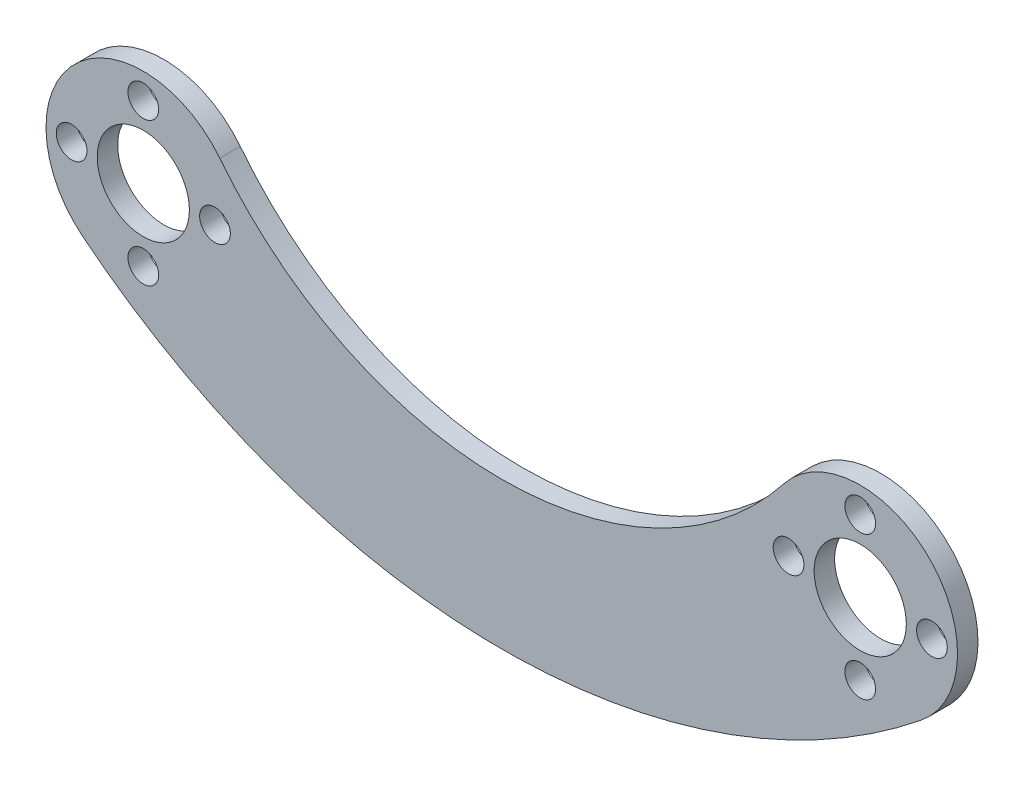
SolidWorks part; units mm, degrees
ref_plane "前视基准面" through (0, 0, 0) normal (0, 0, 1) x (1, 0, 0)
ref_plane "上视基准面" through (0, 0, 0) normal (0, 1, 0) x (1, 0, 0)
ref_plane "右视基准面" through (0, 0, 0) normal (1, 0, 0) x (0, 0, -1)
sketch "草图1" plane through (0, 0, 0) normal (0, 0, 1) x (1, 0, 0)
  line L0 (-54.1945, 0) -> (60.353, 0) construction
  line L1 (0, 45.5042) -> (0, -30.5871) construction
  arc A0 (-27.5281, 5.8669) -> (-40.9709, -7.3891) centre (-35, 0) ccw
  arc A1 (40.9709, -7.3891) -> (27.5281, 5.8669) centre (35, 0) ccw
  arc A2 (-27.5281, 5.8669) -> (27.5281, 5.8669) centre (0, 27.4818) ccw
  arc A3 (-40.9709, -7.3891) -> (40.9709, -7.3891) centre (0, 43.3129) ccw
  dimension "D1" = 19
  dimension "D2" = 19
  dimension "D5" = 35
  dimension "D6" = 65.1867
  dimension "D3" = 70
  dimension "D4" = 35
extrude "凸台-拉伸1" add sketch "草图1" along normal blind 2
sketch "草图2" plane through (0, 0, 2) normal (0, 0, 1) x (1, 0, 0)
  line L0 (-54.4006, 0) -> (57.4537, 0) construction
  line L1 (0, 23.3726) -> (0, -36.024) construction
  circle A1 centre (35, 0) radius 4.5
  circle A2 centre (-35, 0) radius 4.5
  circle A3 centre (-35, 0) radius 7 construction
  circle A4 centre (35, 0) radius 7 construction
  circle A5 centre (-28, 0) radius 1.5
  circle A6 centre (-35, -7) radius 1.5
  circle A7 centre (-42, 0) radius 1.5
  circle A8 centre (-35, 7) radius 1.5
  circle A9 centre (28, 0) radius 1.5
  circle A10 centre (35, 7) radius 1.5
  circle A11 centre (42, 0) radius 1.5
  circle A12 centre (35, -7) radius 1.5
  point P24 (-35, 0)
  point P33 (35, 0)
  dimension "D1" = 9
  dimension "D2" = 9
  dimension "D3" = 14
  dimension "D4" = 14
  dimension "D5" = 3
  dimension "D7" = 3
  dimension "D6" = 4
  dimension "D8" = 4
extrude "切除-拉伸1" cut sketch "草图2" against normal blind 2
